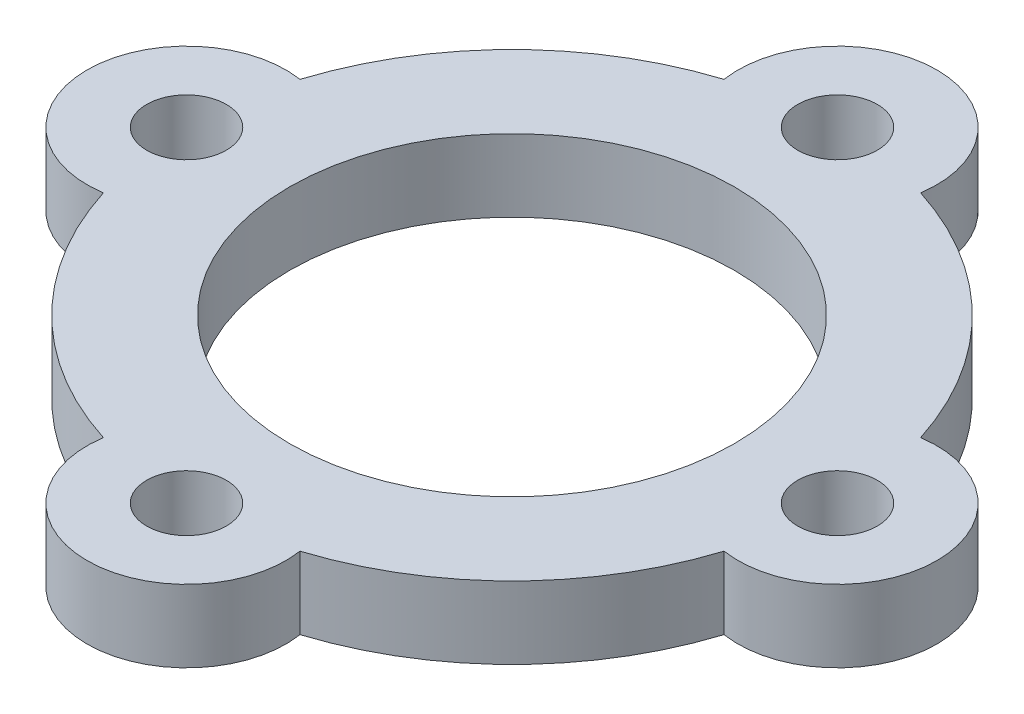
SolidWorks part; units mm, degrees
material "teflon"
ref_plane "Front Plane" through (0, 0, 0) normal (0, 0, 1) x (1, 0, 0)
ref_plane "Top Plane" through (0, 0, 0) normal (0, 1, 0) x (1, 0, 0)
ref_plane "Right Plane" through (0, 0, 0) normal (1, 0, 0) x (0, 0, -1)
sketch "Sketch1" plane through (0, 0, 0) normal (0, 1, 0) x (1, 0, 0)
  line L1 (-11.75, 11.75) -> (11.75, 11.75)
  line L2 (-11.75, 11.75) -> (-11.75, -11.75)
  line L3 (-11.75, -11.75) -> (11.75, -11.75)
  line L4 (11.75, 11.75) -> (11.75, -11.75)
  line L5 (0, -11.75) -> (0, 11.75) construction
  line L6 (-11.75, 0) -> (11.75, 0) construction
  circle A0 centre (0, 0) radius 7.25
  circle A1 centre (0, 0) radius 6.15
  circle A2 centre (0, 9) radius 1.1
  circle A3 centre (9, 0) radius 1.1
  circle A4 centre (0, -9) radius 1.1
  circle A5 centre (-9, 0) radius 1.1
  circle A6 centre (0, 0) radius 6.15
  circle A7 centre (0, 0) radius 9
  circle A8 centre (-9, 0) radius 2.75
  circle A9 centre (0, 9) radius 2.75
  circle A10 centre (0, -9) radius 2.75
  circle A11 centre (9, 0) radius 2.75
  point P6 (0, 0)
  dimension "D1" = 14.5
  dimension "D3" = 2.2
  dimension "D4" = 2.2
  dimension "D9" = 12.3
  dimension "D5" = 9
  dimension "D6" = 9
  dimension "D7" = 2.75
  dimension "D8" = 2.75
  dimension "D2" = 1.1
extrude "Boss-Extrude1" add sketch "Sketch1" along normal blind 2 contours A11 A0 A9 A8 A10 A1 | A8 A0 | A0 A9 | A0 A11 | A10 A0 | A10 A7 A4 A0 | A10 A7 A4 | A8 A7 A5 | A8 A7 A5 A0 | A0 A9 A7 A2 | A7 A9 A2 | A7 A11 A0 A3 | A11 A7 A3 | A11 A7 A9 A0 | A9 A7 A8 A0 | A7 A10 A0 A8 | A11 A0 A10 A7
equation "\"D5@Sketch1\"=((12.5+2)/2)+0.75+1"
equation "\"D6@Sketch1\"=((12.5+2)/2)+0.75+1"
equation "\"D7@Sketch1\"=0.75+2"
equation "\"D8@Sketch1\"=0.75+2"
equation "\"D1@Sketch1\"=12.5+2"
